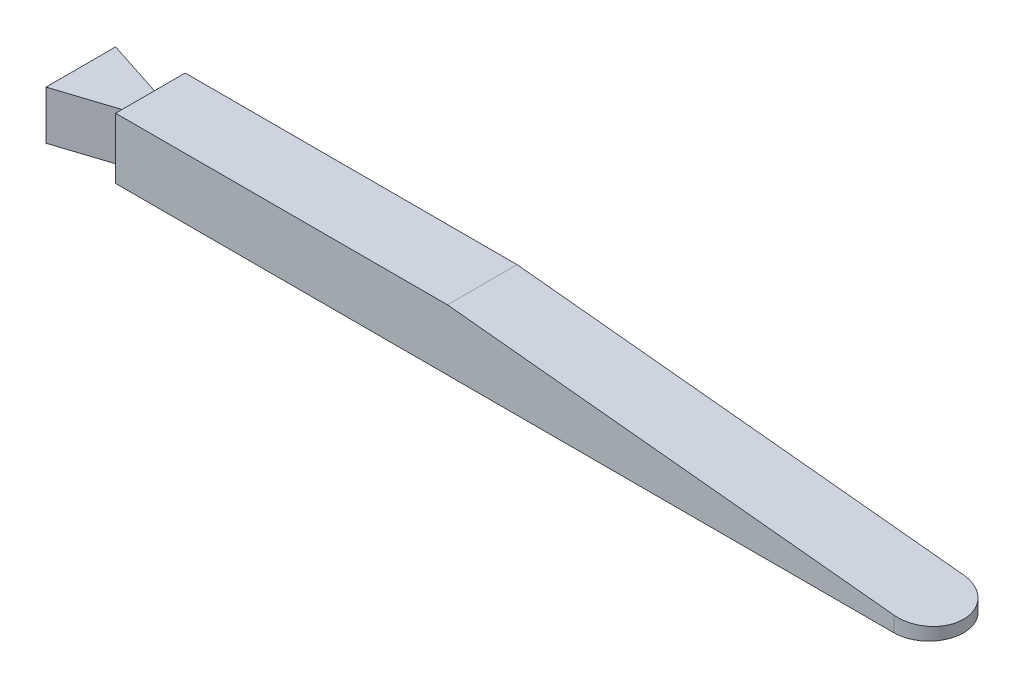
SolidWorks part; units mm, degrees
ref_plane "Front Plane" through (0, 0, 0) normal (0, 0, 1) x (1, 0, 0)
ref_plane "Top Plane" through (0, 0, 0) normal (0, 1, 0) x (1, 0, 0)
ref_plane "Right Plane" through (0, 0, 0) normal (1, 0, 0) x (0, 0, -1)
sketch "Sketch2" plane through (0, 0, 0) normal (0, 1, 0) x (1, 0, 0)
  line L9 (14.3002, -2.54) -> (420.6898, -2.54)
  line L14 (-22.0395, -2.54) -> (-22.0395, -38.8798)
  line L23 (-22.0395, -38.8798) -> (14.3002, -27.1195)
  line L24 (-22.0395, -2.54) -> (14.3002, -14.3002)
  line L25 (14.3002, -38.8798) -> (420.6898, -38.8798)
  line L26 (14.3002, -2.54) -> (14.3002, -14.3002)
  line L27 (14.3002, -27.1195) -> (14.3002, -38.8798)
  arc A2 (420.6898, -38.8798) -> (420.6898, -2.54) centre (420.6898, -20.7099) ccw
  dimension "D4" = 72.067
  dimension "D3" = 11.7602
  dimension "D1" = 36.3398
  dimension "D2" = 72.067
extrude "Boss-Extrude1" add sketch "Sketch2" along normal blind 31.75
sketch "Sketch4" plane through (0, 0, 38.8798) normal (0, 0, 1) x (1, 0, 0)
  line L1 (14.3002, 31.75) -> (420.6898, 31.75) construction
  line L2 (187.5734, 31.75) -> (438.8596, 31.75)
  line L4 (187.5734, 31.75) -> (438.8596, 6.1512)
  line L5 (438.8596, 6.1512) -> (438.8596, 31.75)
extrude "Cut-Extrude2" cut sketch "Sketch4" along direction (0, 0, -1) on the side against the normal through all
sketch "Sketch8" plane through (0, 31.75, 0) normal (0, 1, 0) x (1, 0, 0)
  line L0 (-22.0395, -2.54) -> (14.3002, -14.3002)
  line L1 (14.3002, -14.3002) -> (-22.0395, -2.54) construction
  line L2 (-22.0395, -2.54) -> (-22.0395, -38.8798) construction
  line L4 (-22.0395, -2.54) -> (-22.0395, -38.8798)
  line L5 (-22.0395, -38.8798) -> (14.3002, -27.1195)
  line L6 (14.3002, -27.1195) -> (14.3002, -14.3002)
extrude "Cut-Extrude4" cut sketch "Sketch8" against normal blind 6.35
